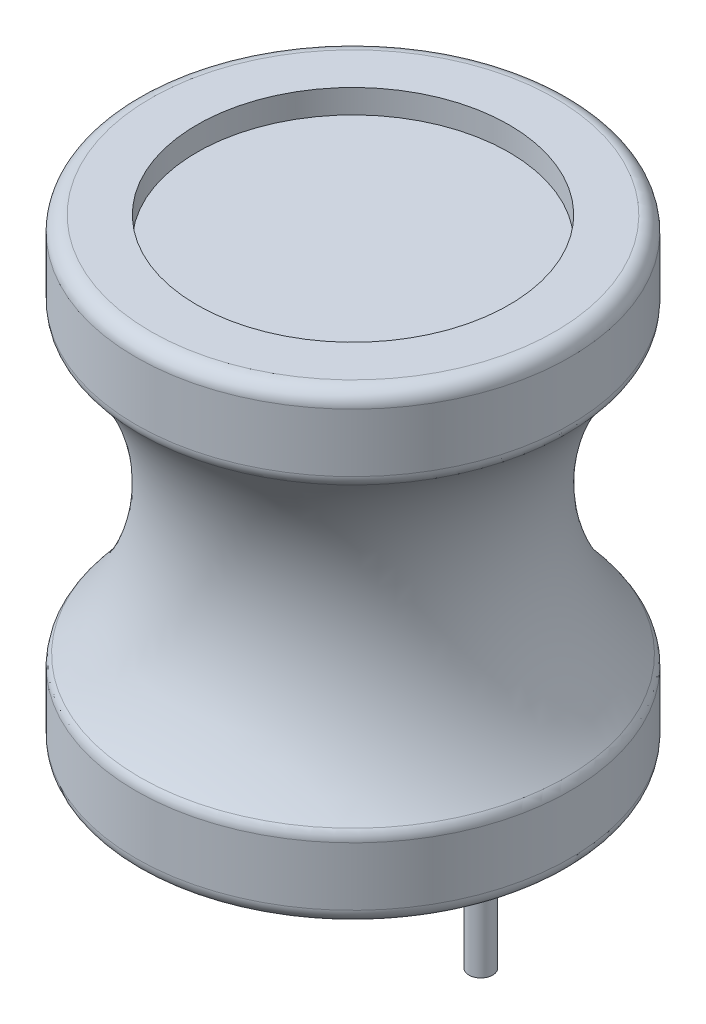
SolidWorks part; units mm, degrees
ref_plane "Front Plane" through (0, 0, 0) normal (0, 0, 1) x (1, 0, 0)
ref_plane "Top Plane" through (0, 0, 0) normal (0, 1, 0) x (1, 0, 0)
ref_plane "Right Plane" through (0, 0, 0) normal (1, 0, 0) x (0, 0, -1)
sketch "Sketch1" plane through (0, 0, 0) normal (1, 0, 0) x (0, 0, -1)
  line L0 (0, 12.5653) -> (0, 7.8) construction
  line L1 (-7.3, 7.3) -> (-7.3, 5.3348)
  line L2 (-6.8, 7.8) -> (-5.25, 7.8)
  line L3 (-12.7166, 0) -> (5.3391, 0) construction
  line L4 (-6.8, -7.8) -> (-5.25, -7.8)
  line L5 (-7.3, -7.3) -> (-7.3, -5.3348)
  line L6 (-5.25, 0) -> (-5.25, 7.8) construction
  line L7 (0, 7) -> (0, -7)
  line L8 (-5.25, 7.8) -> (-5.25, 7)
  line L9 (-5.25, 7) -> (0, 7)
  line L10 (-5.25, 7.8) -> (0, 7.8) construction
  line L11 (0, 7.8) -> (0, 7) construction
  line L12 (0, 7) -> (0, -7) construction
  line L13 (0, 7.8) -> (0, 7) construction
  line L14 (-5.25, -7) -> (0, -7)
  line L15 (-5.25, -7.8) -> (-5.25, -7)
  line L16 (-5.25, -7.8) -> (0, -7.8) construction
  line L17 (0, -7) -> (0, -7.8) construction
  line L18 (0, -7) -> (0, -7.8) construction
  line L19 (0, -7.8) -> (0, -15.4686) construction
  arc A0 (-6.8, 7.8) -> (-7.3, 7.3) centre (-6.8, 7.3) ccw
  arc A1 (-7.3, 5.3348) -> (-7.1713, 5) centre (-6.8, 5.3348) ccw
  arc A2 (-7.1713, 5) -> (-7.1713, -5) centre (-12.7166, 0) cw
  arc A3 (-6.8, -7.8) -> (-7.3, -7.3) centre (-6.8, -7.3) cw
  arc A4 (-7.3, -5.3348) -> (-7.1713, -5) centre (-6.8, -5.3348) cw
  dimension "D4" = 0.5
  dimension "D1" = 15.6
  dimension "D2" = 14.6
  dimension "D3" = 10
  dimension "D5" = 10.5
  dimension "D6" = 10.5
  dimension "D7" = 0.8
revolve "Revolve1" add sketch "Sketch1" angle 360 about L0
sketch "Sketch3" plane through (0, -7, 0) normal (0, -1, 0) x (1, 0, 0)
  line L0 (-4.3, 0) -> (4.3, 0) construction
  line L1 (0, -3.3096) -> (0, 3.3096) construction
  circle A0 centre (-4.3, 0) radius 0.4
  circle A1 centre (4.3, 0) radius 0.4
  point P4 (0, 0)
  point P8 (0, 0)
  dimension "D2" = 0.8
  dimension "D1" = 8.6
extrude "Boss-Extrude1" add sketch "Sketch3" along normal blind 5
